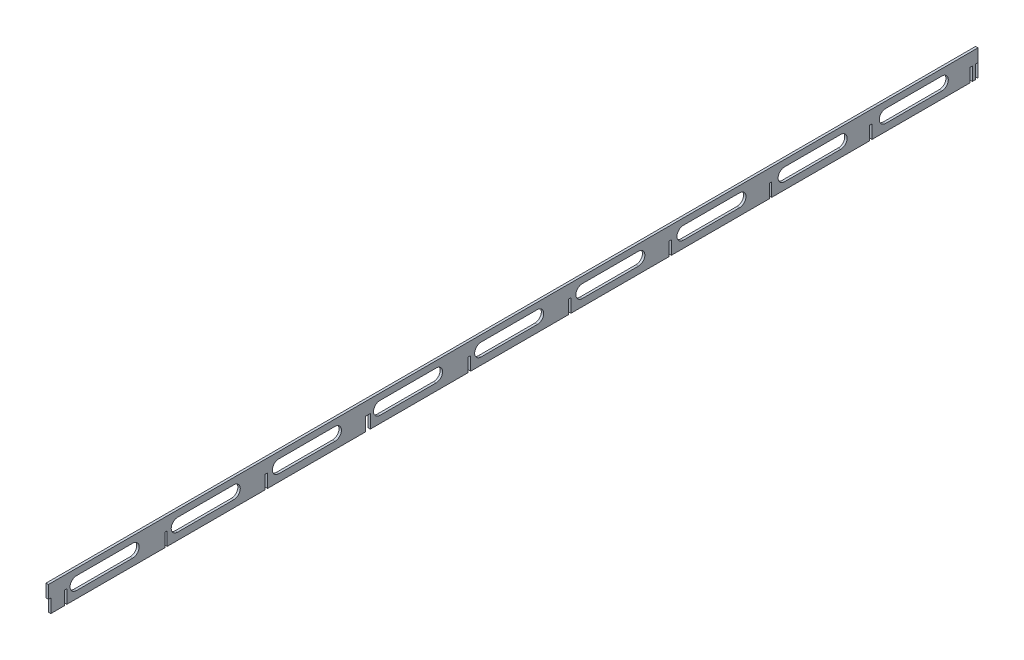
SolidWorks part; units mm, degrees
material "轻木"
ref_plane "前视基准面" through (0, 0, 0) normal (0, 0, 1) x (1, 0, 0)
ref_plane "上视基准面" through (0, 0, 0) normal (0, 1, 0) x (1, 0, 0)
ref_plane "右视基准面" through (0, 0, 0) normal (1, 0, 0) x (0, 0, -1)
other "Configuration Table"
sketch "草图1" plane through (0, 0, 0) normal (0, 0, 1) x (1, 0, 0)
  line L1 (-44.1255, 21.6473) -> (-47.1255, 21.6473)
  line L2 (-44.1255, 21.6473) -> (-44.1255, -11.2586)
  line L3 (-44.1255, -11.2586) -> (-47.1255, -11.2586)
  line L4 (-47.1255, 21.6473) -> (-47.1255, -11.2586)
  point P2 (0, 0)
  point P3 (0, 0)
  dimension "D1" = 3
extrude "凸台-拉伸1" add sketch "草图1" along normal blind 1158
sketch "草图2" plane through (-47.1255, 0, 0) normal (-1, 0, 0) x (0, 0, 1)
  line L0 (1158, -11.2586) -> (0, -11.2586) construction
  line L1 (7.01, -11.2586) -> (10.01, -11.2586)
  line L2 (7.01, -11.2586) -> (7.01, 5.5696)
  line L3 (7.01, 5.5696) -> (10.01, 5.5696)
  line L4 (10.01, -11.2586) -> (10.01, 5.5696)
  line L6 (132.01, -11.2586) -> (135.01, -11.2586)
  line L7 (132.01, -11.2586) -> (132.01, 5.5696)
  line L8 (132.01, 5.5696) -> (135.01, 5.5696)
  line L9 (135.01, -11.2586) -> (135.01, 5.5696)
  line L10 (257.01, -11.2586) -> (260.01, -11.2586)
  line L11 (257.01, -11.2586) -> (257.01, 5.5696)
  line L12 (257.01, 5.5696) -> (260.01, 5.5696)
  line L13 (260.01, -11.2586) -> (260.01, 5.5696)
  line L14 (382.01, -11.2586) -> (385.01, -11.2586)
  line L15 (382.01, -11.2586) -> (382.01, 5.5696)
  line L16 (382.01, 5.5696) -> (385.01, 5.5696)
  line L17 (385.01, -11.2586) -> (385.01, 5.5696)
  line L18 (507.01, -11.2586) -> (510.01, -11.2586)
  line L19 (507.01, -11.2586) -> (507.01, 5.5696)
  line L20 (507.01, 5.5696) -> (510.01, 5.5696)
  line L21 (510.01, -11.2586) -> (510.01, 5.5696)
  line L22 (632.01, -11.2586) -> (635.01, -11.2586)
  line L23 (632.01, -11.2586) -> (632.01, 5.5696)
  line L24 (632.01, 5.5696) -> (635.01, 5.5696)
  line L25 (635.01, -11.2586) -> (635.01, 5.5696)
  line L30 (7.01, -11.2586) -> (132.01, -11.2586) construction
  line L32 (3.01, -11.2586) -> (0.01, -11.2586)
  line L33 (3.01, -11.2586) -> (3.01, 5.5696)
  line L34 (3.01, 5.5696) -> (0.01, 5.5696)
  line L35 (0.01, -11.2586) -> (0.01, 5.5696)
  line L39 (763.01, -11.2586) -> (760.01, -11.2586)
  line L40 (763.01, -11.2586) -> (763.01, 5.5696)
  line L41 (763.01, 5.5696) -> (760.01, 5.5696)
  line L42 (760.01, -11.2586) -> (760.01, 5.5696)
  line L43 (888.01, -11.2586) -> (885.01, -11.2586)
  line L44 (888.01, -11.2586) -> (888.01, 5.5696)
  line L45 (888.01, 5.5696) -> (885.01, 5.5696)
  line L46 (885.01, -11.2586) -> (885.01, 5.5696)
  line L47 (1013.01, -11.2586) -> (1010.01, -11.2586)
  line L48 (1013.01, -11.2586) -> (1013.01, 5.5696)
  line L49 (1013.01, 5.5696) -> (1010.01, 5.5696)
  line L50 (1010.01, -11.2586) -> (1010.01, 5.5696)
  line L51 (1138.01, -11.2586) -> (1135.01, -11.2586)
  line L52 (1138.01, -11.2586) -> (1138.01, 5.5696)
  line L53 (1138.01, 5.5696) -> (1135.01, 5.5696)
  line L54 (1135.01, -11.2586) -> (1135.01, 5.5696)
  line L55 (763.01, -11.2586) -> (888.01, -11.2586) construction
  line L57 (1155.01, -11.2586) -> (1158.01, -11.2586)
  line L58 (1155.01, -11.2586) -> (1155.01, 5.5696)
  line L59 (1155.01, 5.5696) -> (1158.01, 5.5696)
  line L60 (1158.01, -11.2586) -> (1158.01, 5.5696)
  line L61 (45, 5.6473) -> (115, 5.6473) construction
  line L62 (45, 13.6473) -> (115, 13.6473)
  line L63 (760.01, 5.5696) -> (757.01, 5.5696)
  line L64 (757.01, 5.5696) -> (757.01, -11.2586)
  line L66 (757.01, -11.2586) -> (760.01, -11.2586)
  line L67 (45, -2.3527) -> (115, -2.3527)
  line L68 (757.01, 5.5696) -> (760.01, 5.5696)
  line L69 (1158, 21.6473) -> (0, 21.6473) construction
  line L70 (0, 21.6473) -> (0, -11.2586) construction
  line L71 (171, 5.6473) -> (241, 5.6473) construction
  line L72 (171, 13.6473) -> (241, 13.6473)
  line L73 (171, -2.3527) -> (241, -2.3527)
  line L74 (297, 5.6473) -> (367, 5.6473) construction
  line L75 (297, 13.6473) -> (367, 13.6473)
  line L76 (297, -2.3527) -> (367, -2.3527)
  line L77 (423, 5.6473) -> (493, 5.6473) construction
  line L78 (423, 13.6473) -> (493, 13.6473)
  line L79 (423, -2.3527) -> (493, -2.3527)
  line L80 (549, 5.6473) -> (619, 5.6473) construction
  line L81 (549, 13.6473) -> (619, 13.6473)
  line L82 (549, -2.3527) -> (619, -2.3527)
  line L83 (675, 5.6473) -> (745, 5.6473) construction
  line L84 (675, 13.6473) -> (745, 13.6473)
  line L85 (675, -2.3527) -> (745, -2.3527)
  line L86 (801, 5.6473) -> (871, 5.6473) construction
  line L87 (801, 13.6473) -> (871, 13.6473)
  line L88 (801, -2.3527) -> (871, -2.3527)
  line L89 (927, 5.6473) -> (997, 5.6473) construction
  line L90 (927, 13.6473) -> (997, 13.6473)
  line L91 (927, -2.3527) -> (997, -2.3527)
  line L92 (1053, 5.6473) -> (1123, 5.6473) construction
  line L93 (1053, 13.6473) -> (1123, 13.6473)
  line L94 (1053, -2.3527) -> (1123, -2.3527)
  line L95 (757.01, -11.2586) -> (760.01, -11.2586)
  line L98 (45, 5.6473) -> (171, 5.6473) construction
  line L99 (760.01, -11.2586) -> (757.01, -11.2586)
  arc A0 (45, 13.6473) -> (45, -2.3527) centre (45, 5.6473) ccw
  arc A1 (115, -2.3527) -> (115, 13.6473) centre (115, 5.6473) ccw
  arc A2 (171, 13.6473) -> (171, -2.3527) centre (171, 5.6473) ccw
  arc A3 (241, -2.3527) -> (241, 13.6473) centre (241, 5.6473) ccw
  arc A4 (297, 13.6473) -> (297, -2.3527) centre (297, 5.6473) ccw
  arc A5 (367, -2.3527) -> (367, 13.6473) centre (367, 5.6473) ccw
  arc A6 (423, 13.6473) -> (423, -2.3527) centre (423, 5.6473) ccw
  arc A7 (493, -2.3527) -> (493, 13.6473) centre (493, 5.6473) ccw
  arc A8 (549, 13.6473) -> (549, -2.3527) centre (549, 5.6473) ccw
  arc A9 (619, -2.3527) -> (619, 13.6473) centre (619, 5.6473) ccw
  arc A10 (675, 13.6473) -> (675, -2.3527) centre (675, 5.6473) ccw
  arc A11 (745, -2.3527) -> (745, 13.6473) centre (745, 5.6473) ccw
  arc A12 (801, 13.6473) -> (801, -2.3527) centre (801, 5.6473) ccw
  arc A13 (871, -2.3527) -> (871, 13.6473) centre (871, 5.6473) ccw
  arc A14 (927, 13.6473) -> (927, -2.3527) centre (927, 5.6473) ccw
  arc A15 (997, -2.3527) -> (997, 13.6473) centre (997, 5.6473) ccw
  arc A16 (1053, 13.6473) -> (1053, -2.3527) centre (1053, 5.6473) ccw
  arc A17 (1123, -2.3527) -> (1123, 13.6473) centre (1123, 5.6473) ccw
  point P0 (1155.01, -11.2586)
  point P74 (80, 5.6473)
  point P89 (206, 5.6473)
  point P96 (332, 5.6473)
  point P103 (458, 5.6473)
  point P110 (584, 5.6473)
  point P117 (710, 5.6473)
  point P124 (836, 5.6473)
  point P131 (962, 5.6473)
  point P138 (1088, 5.6473)
  line M3 (0, -11.2586) -> (1158, -11.2586)
  line M4 (1158, -11.2586) -> (1158, 21.6473)
  dimension "D5" = 8
  dimension "D2" = 125
  dimension "D3" = 125
  dimension "D4" = 16
  dimension "D6" = 70
  dimension "D7" = 80
  dimension "D8" = 126
  dimension "D11" = 3
  dimension "D12" = 3
  dimension "D13" = 16.8282
  dimension "D1" = 6
  dimension "D10" = 4
  dimension "D9" = 9
extrude "切除-拉伸1" cut sketch "草图2" against normal blind 3 contours L35 L33 L34 M3 | L4 L3 L2 M3 | L67 A1 L62 A0 | L9 L8 L7 M3 | L73 A3 L72 A2 | L13 L12 L11 M3 | L76 A5 L75 A4 | L17 L16 L15 M3 | L79 A7 L78 A6 | L21 L20 L19 M3 | L82 A9 L81 A8 | L25 L24 L23 M3 | L85 A11 L84 A10 | L63 L64 L42 M3 | L42 L40 L41 M3 | L88 A13 L87 A12 | L46 L44 L45 M3 | L91 A15 L90 A14 | L50 L48 L49 M3 | L94 A17 L93 A16 | L54 L52 L53 M3 | L59 L58 M3 M4
